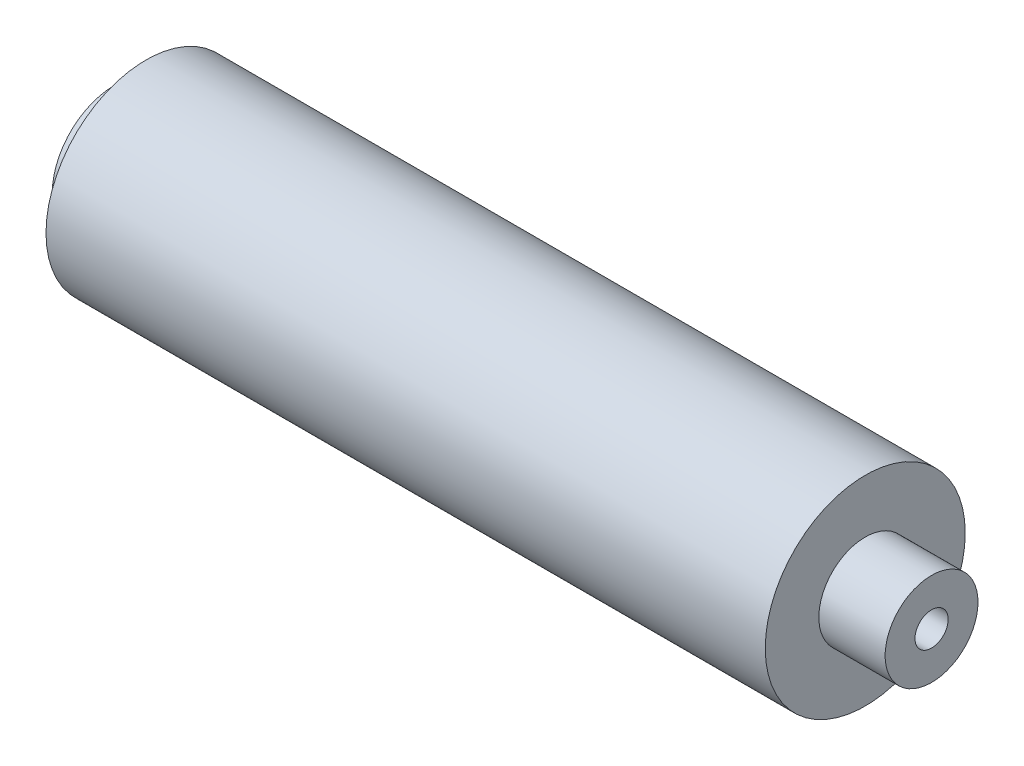
SolidWorks part; units mm, degrees
ref_plane "Front Plane" through (0, 0, 0) normal (0, 0, 1) x (1, 0, 0)
ref_plane "Top Plane" through (0, 0, 0) normal (0, 1, 0) x (1, 0, 0)
ref_plane "Right Plane" through (0, 0, 0) normal (1, 0, 0) x (0, 0, -1)
sketch "Sketch1" plane through (0, 0, 0) normal (1, 0, 0) x (0, 0, -1)
  circle A0 centre (0, 0) radius 15.0762
  dimension "D1" = 30.1523
extrude "Boss-Extrude1" add sketch "Sketch1" along normal blind 118.4446
sketch "Sketch2" plane through (0, 0, 0) normal (-1, 0, 0) x (0, 0, 1)
  circle A0 centre (0, 0) radius 4.5847
  circle A1 centre (0, 0) radius 9.3853
  dimension "D1" = 18.7706
  dimension "D2" = 9.1694
extrude "Boss-Extrude2" add sketch "Sketch2" along normal blind 4.7498
sketch "Sketch3" plane through (118.4446, 0, 0) normal (1, 0, 0) x (0, 0, -1)
  line L0 (-1.7854, 1.75) -> (1.7854, 1.75)
  arc A0 (-1.7854, 1.75) -> (1.7854, 1.75) centre (0, 0) ccw
  dimension "D1" = 5
  dimension "D2" = 3.5707
extrude "Cut-Extrude1" cut sketch "Sketch3" against normal blind 26
sketch "Sketch4" plane through (118.4446, 0, 0) normal (1, 0, 0) x (0, 0, -1)
  circle A0 centre (0, 0) radius 2.5
  arc A1 (-1.7854, 1.75) -> (1.7854, 1.75) centre (0, 0) ccw construction
extrude "Cut-Extrude2" cut sketch "Sketch4" against normal blind 2.6
sketch "Sketch5" plane through (118.4446, 0, 0) normal (1, 0, 0) x (0, 0, -1)
  circle A0 centre (0, 0) radius 7
  circle A1 centre (0, 0) radius 15.0762
  circle A2 centre (0, 0) radius 15.0762 construction
  dimension "D1" = 14
extrude "Cut-Extrude3" cut sketch "Sketch5" against normal blind 10
